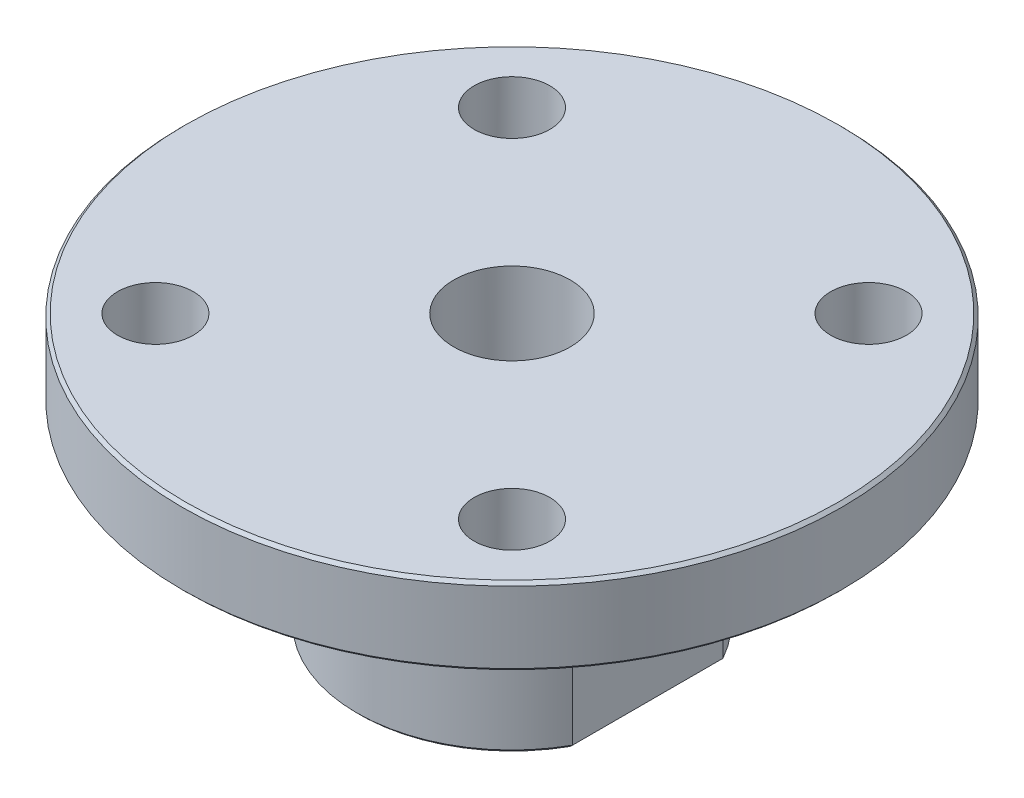
SolidWorks part; units mm, degrees
ref_plane "Front Plane" through (0, 0, 0) normal (0, 0, 1) x (1, 0, 0)
ref_plane "Top Plane" through (0, 0, 0) normal (0, 1, 0) x (1, 0, 0)
ref_plane "Right Plane" through (0, 0, 0) normal (1, 0, 0) x (0, 0, -1)
sketch "Sketch1" plane through (0, 0, 0) normal (0, 0, 1) x (1, 0, 0)
  line L0 (0, 0) -> (0, 50.6683) construction
  line L1 (6.35, 0) -> (6.35, 7.9375)
  line L2 (6.35, 7.9375) -> (13.4937, 7.9375)
  line L3 (13.4937, 7.9375) -> (13.4937, 11.1125)
  line L4 (13.4937, 11.1125) -> (2.3812, 11.1125)
  line L5 (6.35, 0) -> (2.3813, 0)
  line L6 (2.3813, 0) -> (2.3812, 11.1125)
  dimension "D1" = 7.9375
  dimension "D2" = 3.175
  dimension "D3" = 26.9875
  dimension "D4" = 4.7625
  dimension "D5" = 12.7
revolve "Revolve1" add sketch "Sketch1" angle 360 about L0
sketch "Sketch2" plane through (0, 0, 0) normal (0, -1, 0) x (1, 0, 0)
  line L0 (0, 0) -> (0, 11.4258) construction
  line L1 (7.1437, 3.0742) -> (5.5562, -3.0742) construction
  line L2 (-7.1437, -3.0742) -> (-5.5562, -3.0742)
  line L3 (-7.1437, -3.0742) -> (-7.1437, 3.0742)
  line L4 (-7.1437, 3.0742) -> (-5.5562, 3.0742)
  line L5 (-5.5562, -3.0742) -> (-5.5562, 3.0742)
  line L6 (-7.1437, -3.0742) -> (-5.5562, 3.0742) construction
  line L7 (-7.1437, 3.0742) -> (-5.5562, -3.0742) construction
  line L8 (7.1437, -3.0742) -> (5.5562, 3.0742) construction
  line L9 (5.5562, -3.0742) -> (5.5562, 3.0742)
  line L10 (7.1437, 3.0742) -> (5.5562, 3.0742)
  line L11 (7.1437, -3.0742) -> (7.1437, 3.0742)
  line L12 (7.1437, -3.0742) -> (5.5562, -3.0742)
  circle A0 centre (0, 0) radius 6.35 construction
  circle A1 centre (0, 0) radius 6.35 construction
  point P3 (-6.35, 0)
  point P16 (6.35, 0)
  dimension "D1" = 11.1125
extrude "Cut-Extrude1" cut sketch "Sketch2" against normal up to surface (7.9375 mm away) up to face at (0, 7.9375, -13.4937)
sketch "Sketch3" plane through (0, 0, 0) normal (1, 0, 0) x (0, 0, -1)
  circle A0 centre (0, 4.7625) radius 1.55
  dimension "D1" = 3.1
  dimension "D2" = 4.7625
extrude "Cut-Extrude2" cut sketch "Sketch3" against normal through all
sketch "Sketch4" plane through (0, 11.1125, 0) normal (0, 1, 0) x (1, 0, 0)
  line L0 (0, 0) -> (-7.2965, 7.2965) construction
  line L1 (0, 0) -> (0, 10.3187) construction
  circle A0 centre (0, 0) radius 10.3187 construction
  circle A1 centre (-7.2965, 7.2965) radius 1.55
  circle A2 centre (7.2965, 7.2965) radius 1.55
  circle A3 centre (7.2965, -7.2965) radius 1.55
  circle A4 centre (-7.2965, -7.2965) radius 1.55
  dimension "D2" = 3.1
  dimension "D4" = 20.6375
  dimension "D1" = 45
  dimension "D3" = 4
extrude "Cut-Extrude3" cut sketch "Sketch4" against normal through all
chamfer "Chamfer1" distance 0.127 angle 45 6 edges at (5.5562, 0, 0) (0, 0, 6.35) (0, 0, -6.35) (-5.5562, 0, 0) (0, 7.9375, -13.4937) (0, 11.1125, -13.4937)
scale "Scale1" scale about centroid uniform scaling yes scale factor 1.5
